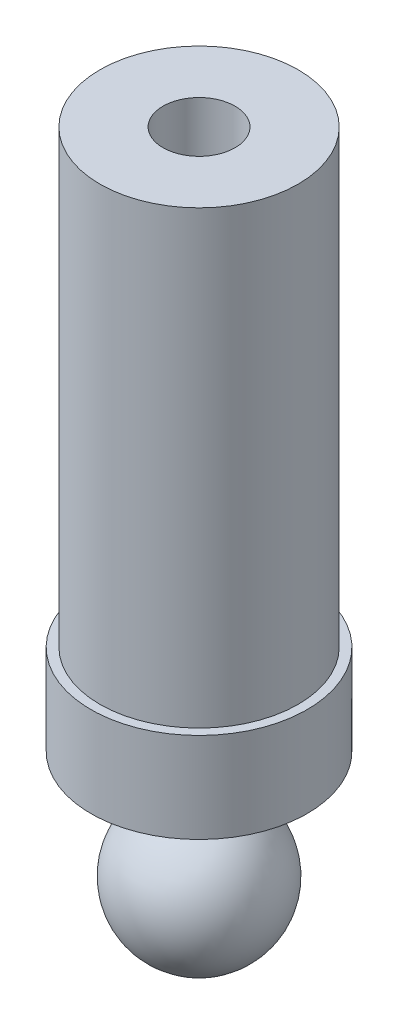
SolidWorks part; units mm, degrees
ref_plane "Front Plane" through (0, 0, 0) normal (0, 0, 1) x (1, 0, 0)
ref_plane "Top Plane" through (0, 0, 0) normal (0, 1, 0) x (1, 0, 0)
ref_plane "Right Plane" through (0, 0, 0) normal (1, 0, 0) x (0, 0, -1)
sketch "Sketch1" plane through (0, 0, 0) normal (0, 1, 0) x (1, 0, 0)
  circle A0 centre (0, 0) radius 6
  dimension "D1" = 12
extrude "Boss-Extrude1" add sketch "Sketch1" along normal blind 45
sketch "Sketch2" plane through (0, 0, 0) normal (0, -1, 0) x (1, 0, 0)
  circle A0 centre (0, 0) radius 4.5
  circle A1 centre (0, 0) radius 6
  circle A2 centre (0, 0) radius 6
  dimension "D1" = 0
  dimension "D2" = 1.5
ref_plane "Plane1" through (0, 5, 0) normal (0, 1, 0) x (1, 0, 0)
sketch "Sketch4" plane through (0, 5, 0) normal (0, 1, 0) x (1, 0, 0)
  circle A0 centre (0, 0) radius 6 construction
  circle A1 centre (0, 0) radius 6
  circle A2 centre (0, 0) radius 5.5
  dimension "D1" = 0.5
sketch "Sketch5" plane through (0, 45, 0) normal (0, 1, 0) x (1, 0, 0)
  circle A0 centre (0, 0) radius 2
  dimension "D1" = 4
ref_plane "Plane2" through (0, 53, 0) normal (0, 1, 0) x (1, 0, 0)
sketch "Sketch6" plane through (0, 53, 0) normal (0, 1, 0) x (1, 0, 0)
  line L0 (-4, 0) -> (4, 0) construction
  line L1 (-4, 0) -> (4, 0)
  arc A0 (-4, 0) -> (4, 0) centre (0, 0) cw
  point P3 (0, 0)
  dimension "D1" = 8
ref_plane "Plane3" through (0, 30, 0) normal (0, 1, 0) x (1, 0, 0)
sketch "Sketch7" plane through (0, 30, 0) normal (0, 1, 0) x (1, 0, 0)
  line L0 (-7.5, 7.5) -> (7.5, -7.5) construction
  line L1 (-7.5, 7.5) -> (7.5, 7.5)
  line L2 (-7.5, 7.5) -> (-7.5, -7.5)
  line L3 (-7.5, -7.5) -> (7.5, -7.5)
  line L4 (7.5, 7.5) -> (7.5, -7.5)
  point P4 (0, 0)
  dimension "D1" = 15
  dimension "D2" = 15
extrude "Cut-Extrude5" cut sketch "Sketch7" along normal blind 25
extrude "Cut-Extrude6" cut sketch "Sketch4" along normal blind 38
extrude "Cut-Extrude7" cut sketch "Sketch5" against normal blind 56 contours A0
sketch "Sketch8" plane through (0, 0, 0) normal (0, -1, 0) x (1, 0, 0)
  circle A0 centre (0, 0) radius 2 construction
  circle A1 centre (0, 0) radius 2
extrude "Boss-Extrude2" add sketch "Sketch8" along normal blind 3 separate body
ref_plane "Plane4" through (0, -6, 0) normal (0, 1, 0) x (1, 0, 0)
sketch "Sketch9" plane through (0, -6, 0) normal (0, 1, 0) x (1, 0, 0)
  line L0 (-4, 0) -> (4, 0) construction
  line L1 (-4, 0) -> (4, 0)
  arc A0 (4, 0) -> (-4, 0) centre (0, 0) ccw construction
  arc A1 (4, 0) -> (-4, 0) centre (0, 0) ccw
revolve "Revolve2" add sketch "Sketch9" angle 360 about L1
